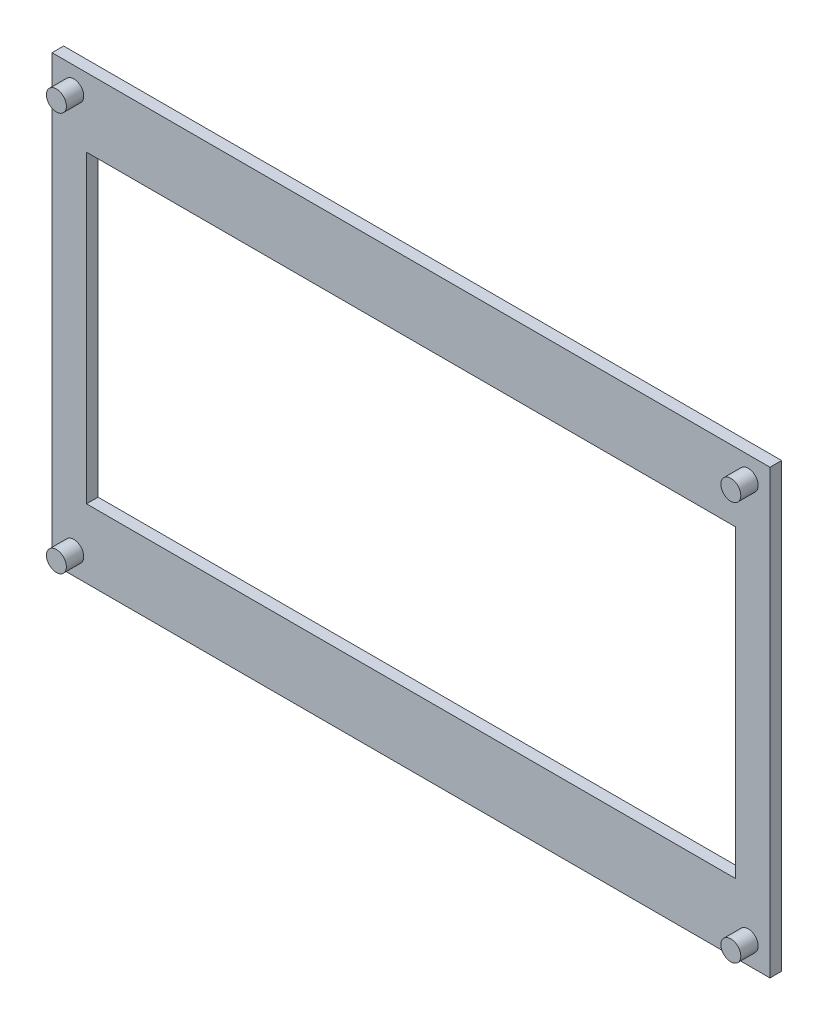
SolidWorks part; units mm, degrees
ref_plane "Front Plane" through (0, 0, 0) normal (0, 0, 1) x (1, 0, 0)
ref_plane "Top Plane" through (0, 0, 0) normal (0, 1, 0) x (1, 0, 0)
ref_plane "Right Plane" through (0, 0, 0) normal (1, 0, 0) x (0, 0, -1)
sketch "Sketch2" plane through (0, 0, 0) normal (0, 0, 1) x (1, 0, 0)
  line L1 (0, 0) -> (99, 0)
  line L2 (0, 0) -> (0, 61)
  line L3 (0, 61) -> (99, 61)
  line L4 (99, 0) -> (99, 61)
  line L5 (4.75, 51.5) -> (94.25, 51.5)
  line L6 (4.75, 51.5) -> (4.75, 9.5)
  line L7 (4.75, 9.5) -> (94.25, 9.5)
  line L8 (94.25, 51.5) -> (94.25, 9.5)
  line L9 (3, 58) -> (96, 58) construction
  line L10 (3, 58) -> (3, 3) construction
  line L11 (3, 3) -> (96, 3) construction
  line L12 (96, 58) -> (96, 3) construction
  point P9 (0, 30.5)
  point P10 (4.75, 30.5)
  point P11 (49.5, 9.5)
  point P12 (49.5, 0)
  point P17 (96, 30.5)
  point P18 (99, 30.5)
  point P19 (49.5, 3)
  dimension "D1" = 99
  dimension "D2" = 61
  dimension "D3" = 42
  dimension "D4" = 89.5
  dimension "D5" = 55
  dimension "D6" = 93
extrude "Boss-Extrude1" add sketch "Sketch2" against normal blind 1.6
sketch "Sketch3" plane through (0, 0, 0) normal (0, 0, 1) x (1, 0, 0)
  circle A0 centre (3, 58) radius 1.375
  circle A1 centre (96, 58) radius 1.375
  circle A2 centre (96, 3) radius 1.375
  circle A3 centre (3, 3) radius 1.375
  dimension "D1" = 2.75
extrude "Boss-Extrude2" add sketch "Sketch3" along normal blind 2.4
